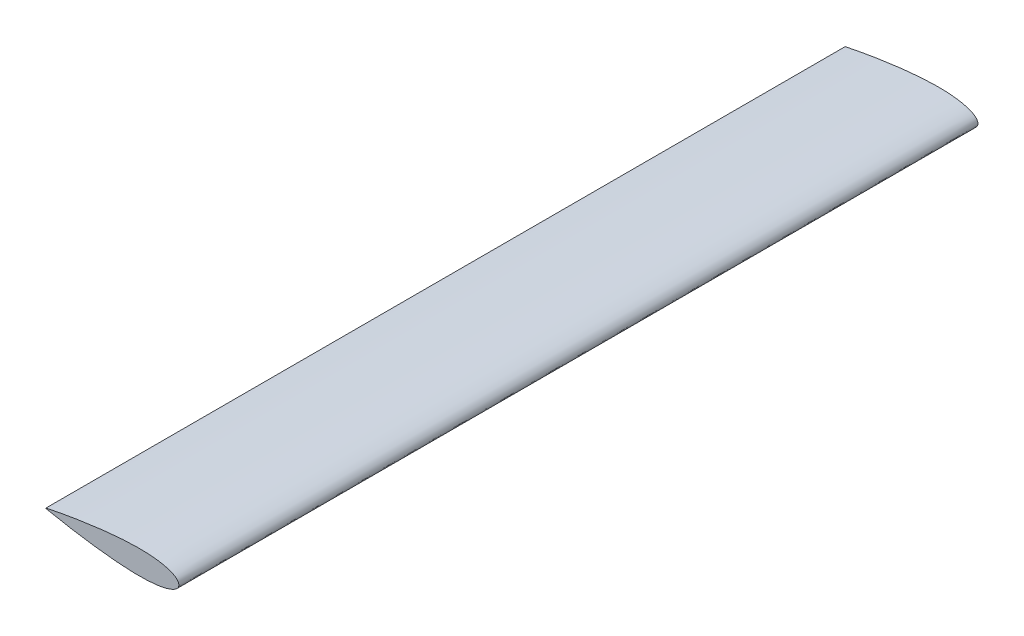
SolidWorks part; units mm, degrees
ref_plane "Alzado" through (0, 0, 0) normal (0, 0, 1) x (1, 0, 0)
ref_plane "Planta" through (0, 0, 0) normal (0, 1, 0) x (1, 0, 0)
ref_plane "Vista lateral" through (0, 0, 0) normal (1, 0, 0) x (0, 0, -1)
sketch "Croquis1" plane through (0, 0, 0) normal (0, 0, 1) x (1, 0, 0)
  line L0 (0, 0) -> (0, -23.5) construction
  line L1 (0, 0) -> (-16, 0) construction
  line L2 (-14.2698, -25.6618) -> (-26, -25.6618)
  line L3 (-26, -25.6618) -> (-26, -33.5)
  line L4 (-26, -33.5) -> (16, -33.5)
  line L5 (16, -33.5) -> (16, 3.8445)
  line L6 (16, 3.8445) -> (-14.2698, 3.8445)
  line L8 (-14.2698, -6.2762) -> (-14.2698, -25.6618)
  line L9 (-14.2698, 3.8445) -> (-26, 3.8445)
  line L10 (-26, 3.8445) -> (-26, -6.2762)
  line L11 (-26, -6.2762) -> (-14.2698, -6.2762)
  circle A0 centre (0, 0) radius 1.5
  dimension "D1" = 3
  dimension "D4" = 16
  dimension "D2" = 23.5
  dimension "D3" = 16
  dimension "D5" = 10
  dimension "D6" = 42
curve "Curva2"
  spline degree 3 poles (266, 0.503, 0) (261.5688, 1.4191, 0) (252.7164, 3.2493, 0) (234.9955, 6.6448, 0) (212.8433, 10.5485, 0) (186.2398, 14.7043, 0) (159.6407, 18.3128, 0) (133.0409, 21.2624, 0) (106.4348, 23.353, 0) (84.237, 24.0962, 0) (66.4893, 23.7999, 0) (53.1677, 23.0109, 0) (39.8211, 21.4881, 0) (28.7128, 19.3599, 0) (19.853, 16.8285, 0) (13.0874, 14.2708, 0) (7.4196, 11.1923, 0) (2.2073, 6.9321, 0) (-1.4404, 0, 0) (2.2073, -6.9321, 0) (7.4196, -11.1923, 0) (13.0874, -14.2708, 0) (19.853, -16.8285, 0) (28.7128, -19.3599, 0) (39.8211, -21.4881, 0) (53.1677, -23.0109, 0) (66.4893, -23.7999, 0) (84.237, -24.0962, 0) (106.4348, -23.353, 0) (133.0409, -21.2624, 0) (159.6407, -18.3128, 0) (186.2398, -14.7043, 0) (212.8433, -10.5485, 0) (234.9955, -6.6448, 0) (252.7164, -3.2493, 0) (261.5688, -1.4191, 0) (266, -0.503, 0) knots 0 0 0 0 0.024604 0.049152 0.098109 0.146905 0.195555 0.244056 0.292409 0.340644 0.364754 0.388905 0.413178 0.437756 0.450305 0.46323 0.477067 0.485036 0.5 0.514964 0.522933 0.53677 0.549695 0.562244 0.586822 0.611095 0.635246 0.659356 0.707591 0.755944 0.804445 0.853095 0.901891 0.950848 0.975396 1 1 1 1
sketch "Croquis6" plane through (0, 0, 0) normal (0, 0, 1) x (1, 0, 0)
  line L2 (-268.433, 0) -> (0, 0) construction
  line L4 (-266, 0.503) -> (-268.433, 0)
  line L5 (-266, -0.503) -> (-268.433, 0)
  spline S2 degree 3 poles (-266, 0.503) (-261.5688, 1.4191) (-252.7164, 3.2493) (-234.9955, 6.6448) (-212.8433, 10.5485) (-186.2398, 14.7043) (-159.6407, 18.3128) (-133.0409, 21.2624) (-106.4348, 23.353) (-84.237, 24.0962) (-66.4893, 23.7999) (-53.1677, 23.0109) (-39.8211, 21.4881) (-28.7128, 19.3599) (-19.853, 16.8285) (-13.0874, 14.2708) (-7.4196, 11.1923) (-2.2073, 6.9321) (1.4404, 0) (-2.2073, -6.9321) (-7.4196, -11.1923) (-13.0874, -14.2708) (-19.853, -16.8285) (-28.7128, -19.3599) (-39.8211, -21.4881) (-53.1677, -23.0109) (-66.4893, -23.7999) (-84.237, -24.0962) (-106.4348, -23.353) (-133.0409, -21.2624) (-159.6407, -18.3128) (-186.2398, -14.7043) (-212.8433, -10.5485) (-234.9955, -6.6448) (-252.7164, -3.2493) (-261.5688, -1.4191) (-266, -0.503) knots 0 0 0 0 0.024604 0.049152 0.098109 0.146905 0.195555 0.244056 0.292409 0.340644 0.364754 0.388905 0.413178 0.437756 0.450305 0.46323 0.477067 0.485036 0.5 0.514964 0.522933 0.53677 0.549695 0.562244 0.586822 0.611095 0.635246 0.659356 0.707591 0.755944 0.804445 0.853095 0.901891 0.950848 0.975396 1 1 1 1
  point P8 (0, 0)
  dimension "D1" = 268.433
sketch "Croquis7" plane through (0, 0, 0) normal (0, 0, 1) x (1, 0, 0)
  line L0 (-266, 0.503) -> (-268.433, 0) construction
  line L1 (-266, 0.503) -> (-268.433, 0) construction
  line L2 (-266, -0.503) -> (-268.433, 0) construction
  line L3 (-266, -0.503) -> (-268.433, 0) construction
  line L4 (-266, -0.503) -> (-266, 0.503)
  spline S0 degree 3 poles (-1155.1432, 1765.3014) (-594.7387, -117.8294) (-424.6464, -29.6947) (-234.9955, 6.6448) (-212.8433, 10.5485) (-186.2398, 14.7043) (-159.6407, 18.3128) (-133.0409, 21.2624) (-106.4348, 23.353) (-84.237, 24.0962) (-66.4893, 23.7999) (-53.1677, 23.0109) (-39.8211, 21.4881) (-28.7128, 19.3599) (-19.853, 16.8285) (-13.0874, 14.2708) (-7.4196, 11.1923) (-2.2073, 6.9321) (1.4404, 0) (-2.2073, -6.9321) (-7.4196, -11.1923) (-13.0874, -14.2708) (-19.853, -16.8285) (-28.7128, -19.3599) (-39.8211, -21.4881) (-53.1677, -23.0109) (-66.4893, -23.7999) (-84.237, -24.0962) (-106.4348, -23.353) (-133.0409, -21.2624) (-159.6407, -18.3128) (-186.2398, -14.7043) (-212.8433, -10.5485) (-234.9955, -6.6448) (-424.6458, 29.6946) (-594.7376, 117.8288) (-1155.1376, -1765.2827) knots -0.951855 -0.951855 -0.951855 -0.951855 0.024604 0.049152 0.098109 0.146905 0.195555 0.244056 0.292409 0.340644 0.364754 0.388905 0.413178 0.437756 0.450305 0.46323 0.477067 0.485036 0.5 0.514964 0.522933 0.53677 0.549695 0.562244 0.586822 0.611095 0.635246 0.659356 0.707591 0.755944 0.804445 0.853095 0.901891 0.950848 0.975396 1.951852 1.951852 1.951852 1.951852 only from (-266, 0.503) to (-266, -0.503) construction
  spline S1 degree 3 poles (-266, 0.503) (-261.5688, 1.4191) (-252.7164, 3.2493) (-234.9955, 6.6448) (-212.8433, 10.5485) (-186.2398, 14.7043) (-159.6407, 18.3128) (-133.0409, 21.2624) (-106.4348, 23.353) (-84.237, 24.0962) (-66.4893, 23.7999) (-53.1677, 23.0109) (-39.8211, 21.4881) (-28.7128, 19.3599) (-19.853, 16.8285) (-13.0874, 14.2708) (-7.4196, 11.1923) (-2.2073, 6.9321) (1.4404, 0) (-2.2073, -6.9321) (-7.4196, -11.1923) (-13.0874, -14.2708) (-19.853, -16.8285) (-28.7128, -19.3599) (-39.8211, -21.4881) (-53.1677, -23.0109) (-66.4893, -23.7999) (-84.237, -24.0962) (-106.4348, -23.353) (-133.0409, -21.2624) (-159.6407, -18.3128) (-186.2398, -14.7043) (-212.8433, -10.5485) (-234.9955, -6.6448) (-252.7164, -3.2493) (-261.5688, -1.4191) (-266, -0.503) knots 0 0 0 0 0.024604 0.049152 0.098109 0.146905 0.195555 0.244056 0.292409 0.340644 0.364754 0.388905 0.413178 0.437756 0.450305 0.46323 0.477067 0.485036 0.5 0.514964 0.522933 0.53677 0.549695 0.562244 0.586822 0.611095 0.635246 0.659356 0.707591 0.755944 0.804445 0.853095 0.901891 0.950848 0.975396 1 1 1 1
  point P2 (0, 0)
extrude "Saliente-Extruir1" add sketch "Croquis7" along normal mid plane 1600
